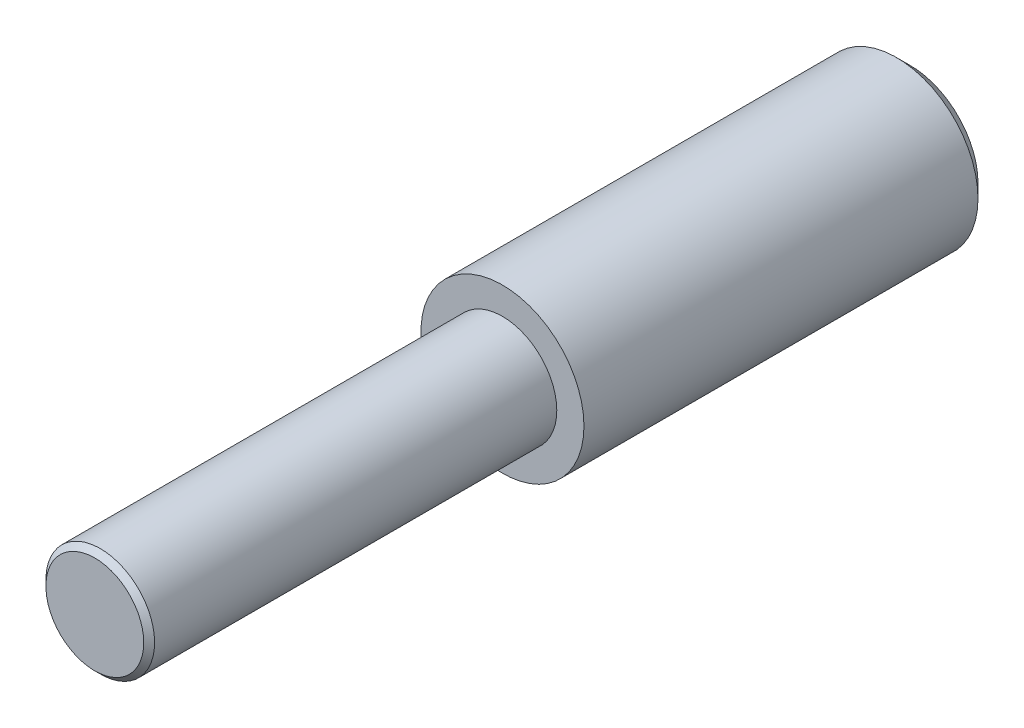
SolidWorks part; units mm, degrees
ref_plane "Спереди" through (0, 0, 0) normal (0, 0, 1) x (1, 0, 0)
ref_plane "Сверху" through (0, 0, 0) normal (0, 1, 0) x (1, 0, 0)
ref_plane "Справа" through (0, 0, 0) normal (1, 0, 0) x (0, 0, -1)
sketch "Эскиз1" plane through (0, 0, 0) normal (0, 0, 1) x (1, 0, 0)
  circle A0 centre (0, 0) radius 3
  dimension "D1" = 6
extrude "Основание-Вытянуть" add sketch "Эскиз1" along normal blind 15
sketch "Эскиз2" plane through (0, 0, 15) normal (0, 0, 1) x (1, 0, 0)
  circle A0 centre (0, 0) radius 2
  dimension "D1" = 4
extrude "Бобышка-Вытянуть1" add sketch "Эскиз2" along normal blind 15
chamfer "Фаска1" distance 0.2 angle 45
chamfer "Фаска2" distance 0.5 angle 45
